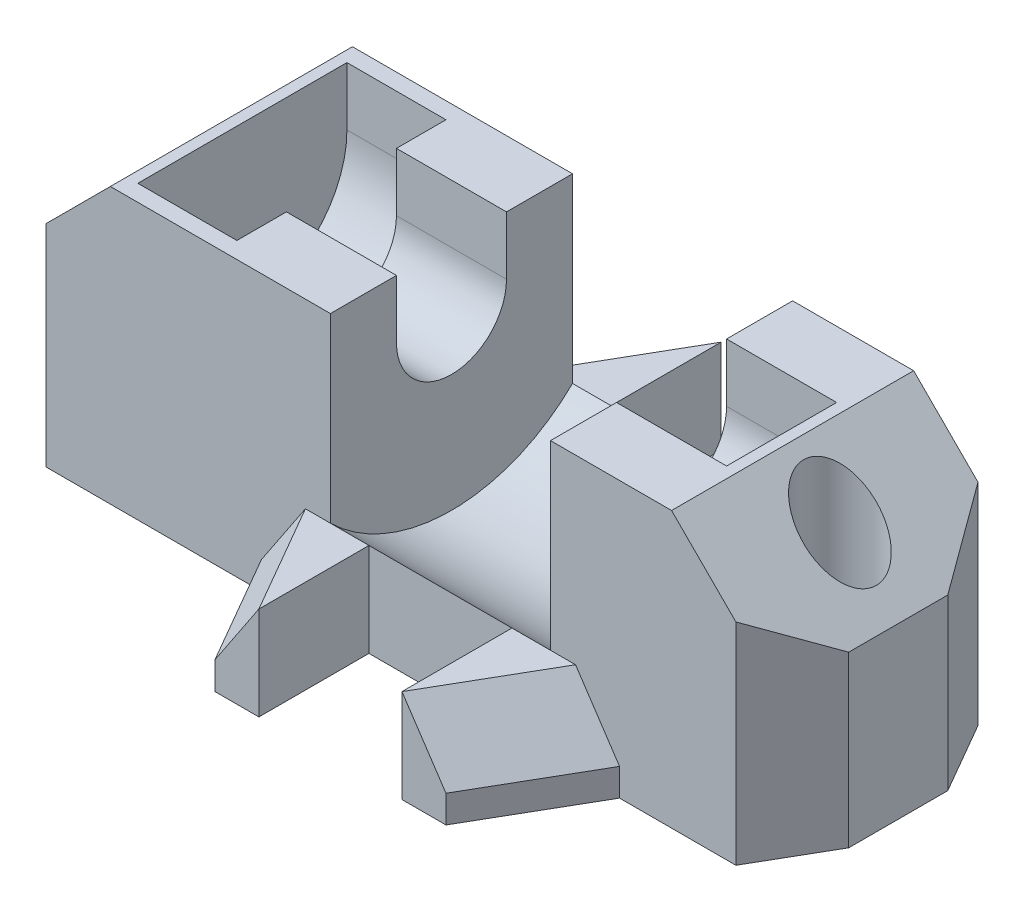
SolidWorks part; units mm, degrees
material "ABS"
ref_plane "Ebene vorne" through (0, 0, 0) normal (0, 0, 1) x (1, 0, 0)
ref_plane "Ebene oben" through (0, 0, 0) normal (0, 1, 0) x (1, 0, 0)
ref_plane "Ebene rechts" through (0, 0, 0) normal (1, 0, 0) x (0, 0, -1)
sketch "Skizze1" plane through (0, 0, 0) normal (0, 1, 0) x (1, 0, 0)
  line L0 (-0.7736, 5.5) -> (-30.5736, 5.5) construction
  line L1 (-16.4236, 12) -> (-10.4236, 12) construction
  line L2 (-16.4236, 12) -> (-16.4236, -1) construction
  line L3 (-16.4236, -1) -> (-10.4236, -1) construction
  line L4 (-10.4236, 12) -> (-10.4236, -1) construction
  line L5 (-13.4236, 12) -> (-13.4236, -1) construction
  line L6 (-3.4236, 8) -> (-23.4236, 8) construction
  line L7 (-3.4236, 8) -> (-3.4236, 3) construction
  line L8 (-3.4236, 3) -> (-23.4236, 3) construction
  line L9 (-23.4236, 8) -> (-23.4236, 3) construction
  line L10 (-23.4236, 10.25) -> (-27.9236, 10.25) construction
  line L11 (-23.4236, 10.25) -> (-23.4236, 0.75) construction
  line L12 (-23.4236, 0.75) -> (-27.9236, 0.75) construction
  line L13 (-27.9236, 10.25) -> (-27.9236, 0.75) construction
  line L14 (-17.4236, 13) -> (-16.4236, 13) construction
  line L15 (-17.4236, 13) -> (-17.4236, -2) construction
  line L16 (-17.4236, -2) -> (-16.4236, -2) construction
  line L17 (-16.4236, 13) -> (-16.4236, -2) construction
  line L18 (-9.4236, 13) -> (-10.4236, 13) construction
  line L19 (-9.4236, 13) -> (-9.4236, -2) construction
  line L20 (-9.4236, -2) -> (-10.4236, -2) construction
  line L21 (-10.4236, 13) -> (-10.4236, -2) construction
  line L23 (0, 11) -> (-31.3472, 11)
  line L24 (-31.3472, 0) -> (0, 0)
  line L25 (0, 11) -> (1.8764, 7.75)
  line L26 (1.8764, 7.75) -> (1.8764, 3.25)
  line L27 (1.8764, 3.25) -> (0, 0)
  line L28 (-15.6736, 11) -> (-15.6736, 0) construction
  line L29 (-33.2236, 3.25) -> (-31.3472, 0)
  line L30 (-33.2236, 7.75) -> (-33.2236, 3.25)
  line L31 (-31.3472, 11) -> (-33.2236, 7.75)
  line L32 (-9.4236, 10.25) -> (-8.4236, 10.25) construction
  line L33 (-9.4236, 10.25) -> (-9.4236, 0.75) construction
  line L34 (-9.4236, 0.75) -> (-8.4236, 0.75) construction
  line L35 (-8.4236, 10.25) -> (-8.4236, 0.75) construction
  line L36 (-17.4236, 10.25) -> (-18.4236, 10.25) construction
  line L37 (-17.4236, 10.25) -> (-17.4236, 0.75) construction
  line L38 (-17.4236, 0.75) -> (-18.4236, 0.75) construction
  line L39 (-18.4236, 10.25) -> (-18.4236, 0.75) construction
  circle A0 centre (-0.7736, 5.5) radius 1.65
  circle A1 centre (-30.5736, 5.5) radius 1.65
  circle A2 centre (6.5764, 11.5) radius 4.25 construction
  point P8 (-16.4236, 5.5)
  point P11 (-13.4236, 5.5)
  point P20 (-27.9236, 5.5)
  point P21 (-3.4236, 5.5)
  point P24 (2.3264, 11.5)
  point P25 (0.8764, 5.5)
  point P26 (-2.4236, 5.5)
  point P35 (-28.9236, 5.5)
  point P42 (1.8764, 5.5)
  point P49 (-32.2236, 5.5)
  point P56 (-8.4236, 5.5)
  dimension "D2" = 3.3
  dimension "D24" = 8.5
  dimension "D1" = 6
  dimension "D3" = 20
  dimension "D4" = 4.5
  dimension "D5" = 9.5
  dimension "D6" = 5
  dimension "D7" = 1
  dimension "D8" = 1.45
  dimension "D9" = 13
  dimension "D10" = 8
  dimension "D11" = 5
  dimension "D12" = 5
  dimension "D13" = 1
  dimension "D14" = 29.8
  dimension "D15" = 0.5
  dimension "D16" = 15
  dimension "D17" = 1
  dimension "D18" = 1
  dimension "D19" = 1
  dimension "D20" = 60
  dimension "D21" = 4.5
  dimension "D22" = 1
  dimension "D23" = 20
  dimension "D25" = 10.3
  dimension "D26" = 10
  dimension "D27" = 9.5
  dimension "D28" = 5.3
extrude "Aufsatz-Linear austragen1" add sketch "Skizze1" along normal blind 12.5
sketch "Skizze2" plane through (1.8764, 0, 0) normal (1, 0, 0) x (0, 0, -1)
  line L0 (7.75, 0) -> (11, 0) construction
  line L1 (3.25, 0) -> (7.75, 0) construction
  line L2 (0, 0) -> (3.25, 0) construction
  line L3 (0, 12.5) -> (0, 0) construction
  line L4 (11, 12.5) -> (11, 0) construction
  line L5 (7.75, 0) -> (11, 0) construction
  line L6 (3.25, 0) -> (7.75, 0) construction
  line L7 (0, 0) -> (3.25, 0) construction
  line L8 (0, 12.5) -> (0, 0) construction
  line L9 (11, 12.5) -> (11, 0) construction
  line L10 (5.5, 0) -> (5.5, 9.85) construction
  line L14 (3.25, 12.5) -> (7.75, 12.5) construction
  circle A0 centre (5.5, 9.85) radius 6.5 construction
  circle A1 centre (5.5, 9.85) radius 7.5 construction
  circle A2 centre (5.5, 9.85) radius 7.85
  circle A3 centre (5.5, 9.85) radius 2.5
  point P11 (5.5, 2)
  point P13 (5.5, 12.35)
  point P14 (5.5, 17.7)
  point P15 (5.5, 16.35)
  dimension "D1" = 13
  dimension "D2" = 15
  dimension "D3" = 15.7
  dimension "D5" = 5
  dimension "D4" = 2
  dimension "D6" = 3.85
  dimension "D7" = 0.15
extrude "Schnitt-Linear austragen1" cut sketch "Skizze2" against normal blind 10 from offset 10.3
sketch "Skizze3" plane through (1.8764, 0, 0) normal (1, 0, 0) x (0, 0, -1)
  line L0 (3, 12.5) -> (8, 12.5)
  line L1 (3, 9.85) -> (3, 12.5)
  line L2 (8, 9.85) -> (8, 12.5)
  line L3 (3.25, 12.5) -> (7.75, 12.5) construction
  circle A0 centre (5.5, 9.85) radius 2.5 construction
  circle A1 centre (5.5, 9.85) radius 2.5
  line M2 (7.75, 0) -> (7.75, 12.5)
  line M3 (7.75, 12.5) -> (3.25, 12.5)
  line M4 (3.25, 12.5) -> (3.25, 0)
extrude "Schnitt-Linear austragen2" cut sketch "Skizze3" against normal blind 20 from offset 5.3 contours A1 M2 M3 M4 | A1 L2 L0 M2 | A1 L0 L1 M4 | A1 M2 M4 | A1 M4 | A1 M2
sketch "Skizze4" plane through (-23.4236, 0, 0) normal (1, 0, 0) x (0, 0, -1)
  line L0 (10.25, 9.85) -> (10.25, 12.5)
  line L1 (0.75, 9.85) -> (0.75, 12.5)
  line L2 (0.75, 12.5) -> (10.25, 12.5)
  line L3 (8, 12.5) -> (3, 12.5) construction
  circle A0 centre (5.5, 9.85) radius 2.5 construction
  arc A1 (3, 9.85) -> (8, 9.85) centre (5.5, 9.85) ccw construction
  circle A2 centre (5.5, 9.85) radius 4.75
  line M1 (3, 12.5) -> (3, 9.85)
  arc M2 (3, 9.85) -> (8, 9.85) centre (5.5, 9.85) ccw
  line M3 (8, 9.85) -> (8, 12.5)
  line M4 (8, 12.5) -> (3, 12.5)
  dimension "D1" = 9.5
extrude "Schnitt-Linear austragen3" cut sketch "Skizze4" against normal blind 4.5 contours A2 L0 L2 | A2 L2 M3 M2 M1 | M4 M1 M2 M3 | A2 L2 L1
sketch "Skizze5" plane through (0, 0, 0) normal (0, 0, 1) x (1, 0, 0)
  line L0 (1.8764, 12.5) -> (-2.9236, 12.5)
  line L1 (-2.9236, 12.5) -> (1.8764, 7.7)
  line L2 (1.8764, 7.7) -> (1.8764, 12.5)
  line L3 (-33.2236, 12.5) -> (-28.4236, 12.5)
  line L4 (-28.4236, 12.5) -> (-33.2236, 7.7)
  line L5 (-33.2236, 7.7) -> (-33.2236, 12.5)
  line L6 (-8.4236, 12.5) -> (0, 12.5) construction
  line L7 (-33.2236, 12.5) -> (-33.2236, 0) construction
  line L8 (1.8764, 12.5) -> (1.8764, 0) construction
  line L9 (-3.4236, 12.5) -> (-2.4236, 12.5) construction
  point P12 (-3.4236, 12.5)
  point P13 (-2.4236, 12.5)
  point P18 (-2.9236, 12.5)
  dimension "D1" = 45
extrude "Schnitt-Linear austragen4" cut sketch "Skizze5" against normal up to surface (11 mm away)
sketch "Skizze6" plane through (0, 0, 0) normal (0, -1, 0) x (1, 0, 0)
  line L0 (-18.4236, -11) -> (-18.4236, 0) construction
  line L1 (-8.4236, 0) -> (-8.4236, -11) construction
  line L2 (-18.4236, -11) -> (-18.4236, 0) construction
  line L3 (-8.4236, 0) -> (-8.4236, -11) construction
  line L4 (-8.4236, -5.5) -> (-18.4236, -5.5) construction
  line L5 (-13.4236, 0) -> (-13.4236, -11) construction
  line L6 (-31.3472, 0) -> (0, 0) construction
  line L7 (0, -11) -> (-31.3472, -11) construction
  line L8 (-16.6736, 1) -> (-10.1736, 1) construction
  line L9 (-16.6736, 0) -> (-16.6736, 5)
  line L10 (-10.1736, 0) -> (-10.1736, 5)
  line L11 (-16.6736, -12) -> (-10.1736, -12) construction
  line L12 (-10.1736, 5) -> (-8.1736, 5)
  line L13 (-8.1736, 5) -> (-5.2869, 0)
  line L14 (-16.6736, 5) -> (-18.6736, 5)
  line L15 (-18.6736, 5) -> (-21.5604, 0)
  line L16 (-10.1736, 0) -> (-5.2869, 0)
  line L17 (-16.6736, 0) -> (-21.5604, 0)
  line L18 (-18.6736, -16) -> (-21.5604, -11)
  line L19 (-16.6736, -16) -> (-18.6736, -16)
  line L20 (-16.6736, -11) -> (-16.6736, -16)
  line L21 (-16.6736, -11) -> (-21.5604, -11)
  line L22 (-10.1736, -11) -> (-5.2869, -11)
  line L23 (-8.1736, -16) -> (-5.2869, -11)
  line L24 (-10.1736, -16) -> (-8.1736, -16)
  line L25 (-10.1736, -11) -> (-10.1736, -16)
  point P12 (-13.4236, -5.5)
  dimension "D1" = 6.5
  dimension "D2" = 13
  dimension "D3" = 4
  dimension "D4" = 2
  dimension "D5" = 60
  dimension "D6" = 60
extrude "Aufsatz-Linear austragen2" add sketch "Skizze6" against normal up to vertex (12.5 mm away)
chamfer "Fase1" distance 3 angle 30 4 edges at (-6.7302, 4.2489, -13.5) (-20.117, 4.2489, -13.5) (-6.7302, 4.2489, 2.5) (-20.117, 4.2489, 2.5)
